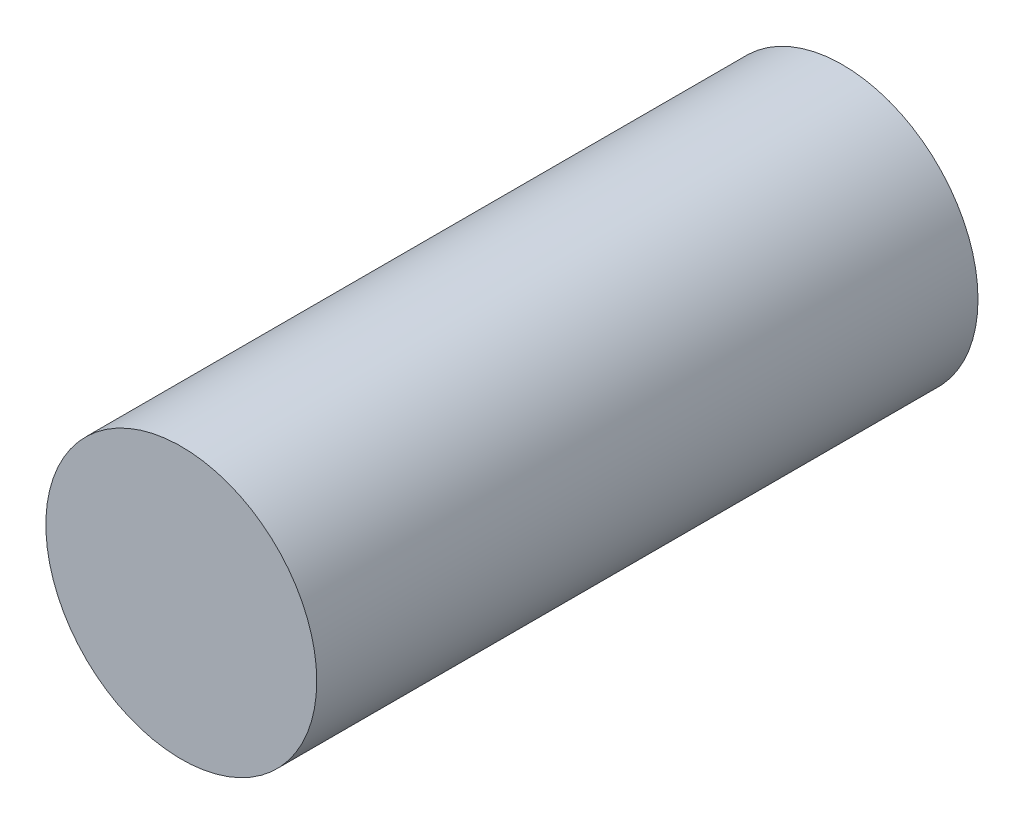
SolidWorks part; units mm, degrees
ref_plane "Front Plane" through (0, 0, 0) normal (0, 0, 1) x (1, 0, 0)
ref_plane "Top Plane" through (0, 0, 0) normal (0, 1, 0) x (1, 0, 0)
ref_plane "Right Plane" through (0, 0, 0) normal (1, 0, 0) x (0, 0, -1)
sketch "Planform" plane through (0, 0, 0) normal (0, 1, 0) x (1, 0, 0)
  line L0 (0, 0) -> (0, -7497.1177)
  line L1 (-17711.9405, -11444.2752) -> (-17711.9405, -14068.2664)
  line L2 (0, -1874.2794) -> (-17711.9405, -12100.273) construction
  line L3 (0, -1874.2794) -> (-6644.0672, -1874.2794) construction
  line L4 (0, 0) -> (-17711.9405, -11444.2752)
  line L5 (0, -7497.1177) -> (-17711.9405, -14068.2664)
  dimension "D1" = 7497.1177
  dimension "D2" = 2623.9912
  dimension "D3" = 1874.2794
  dimension "D4" = 655.9978
  dimension "D5" = 30
  dimension "D6" = 17711.9405
sketch "Sketch1" plane through (0, 0, 0) normal (0, 0, 1) x (1, 0, 0)
  circle A0 centre (0, 0) radius 1209.8064
  dimension "D1" = 2419.6129
extrude "Nacelle body" add sketch "Sketch1" along normal blind 5906.115
sketch "Black front" plane through (0, 0, 5906.115) normal (0, 0, 1) x (1, 0, 0)
  line L0 (59.2242, 1082.815) -> (229.8908, 1082.815) construction
sketch "Location" plane through (0, 0, 0) normal (0, 1, 0) x (1, 0, 0)
  line L0 (-1209.8064, -1066.8892) -> (1209.8064, -1066.8892)
  line L1 (1209.8064, 0) -> (-1209.8064, 0)
  line L2 (1209.8064, 0) -> (1209.8064, -5906.115)
  line L3 (1209.8064, -5906.115) -> (-1209.8064, -5906.115)
  line L4 (-1209.8064, 0) -> (-1209.8064, -5906.115)
  line L5 (-1209.8064, 0) -> (1209.8064, -5906.115)
  line L6 (1209.8064, 0) -> (-1209.8064, -5906.115)
  line L7 (1209.8064, -2953.0575) -> (-1209.8064, -2953.0575)
  point P11 (0, -2953.0575)
  dimension "D1" = 2419.6129
  dimension "D2" = 4839.2257
equation "\"Diameter\"= 7.938362438"
equation "\"Length\" = 19.37701766"
equation "\"D1@Sketch1\"=\"Diameter\""
equation "\"D1@Nacelle body\"=\"Length\""
equation "\"D2@Location\"=\"Diameter\"*2"
